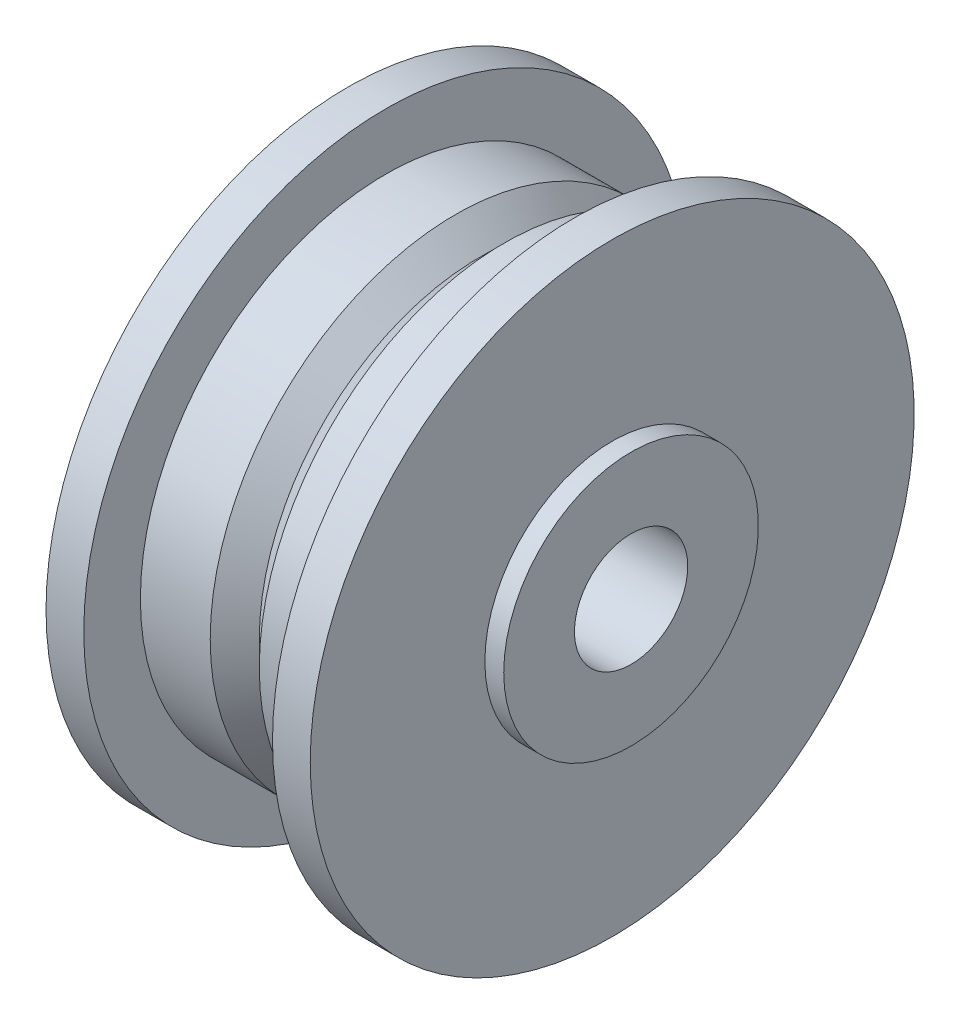
SolidWorks part; units mm, degrees
ref_plane "Front Plane" through (0, 0, 0) normal (0, 0, 1) x (1, 0, 0)
ref_plane "Top Plane" through (0, 0, 0) normal (0, 1, 0) x (1, 0, 0)
ref_plane "Right Plane" through (0, 0, 0) normal (1, 0, 0) x (0, 0, -1)
sketch "Sketch1" plane through (0, 0, 0) normal (0, 0, 1) x (1, 0, 0)
  line L0 (0, 0) -> (726.2136, 0) construction
  line L1 (0, 0) -> (0, 67.4757)
  line L2 (0, 67.4757) -> (10, 67.4757)
  line L3 (10, 67.4757) -> (10, 160)
  line L4 (10, 160) -> (30, 160)
  line L5 (30, 160) -> (30, 130)
  line L6 (30, 130) -> (67, 130)
  line L7 (67, 130) -> (80, 117)
  line L8 (80, 117) -> (93, 130)
  line L9 (93, 130) -> (130, 130)
  line L10 (130, 130) -> (130, 160)
  line L11 (130, 160) -> (150, 160)
  line L12 (150, 160) -> (150, 67.4757)
  line L13 (150, 67.4757) -> (160, 67.4757)
  line L14 (160, 67.4757) -> (160, 0)
  line L15 (0, 0) -> (160, 0)
  point P15 (111.5, 130)
  dimension "D1" = 100
  dimension "D2" = 140
  dimension "D3" = 10
  dimension "D4" = 10
  dimension "D5" = 160
  dimension "D6" = 160
  dimension "D7" = 130
  dimension "D8" = 130
  dimension "D9" = 26
  dimension "D10" = 37
  dimension "D11" = 37
  dimension "D12" = 20
  dimension "D13" = 20
revolve "Revolve1" add sketch "Sketch1" angle 360 about L0
sketch "Sketch2" plane through (160, 0, 0) normal (1, 0, 0) x (0, 0, -1)
  circle A0 centre (0, 0) radius 30
  dimension "D1" = 60
extrude "Cut-Extrude1" cut sketch "Sketch2" against normal through all
